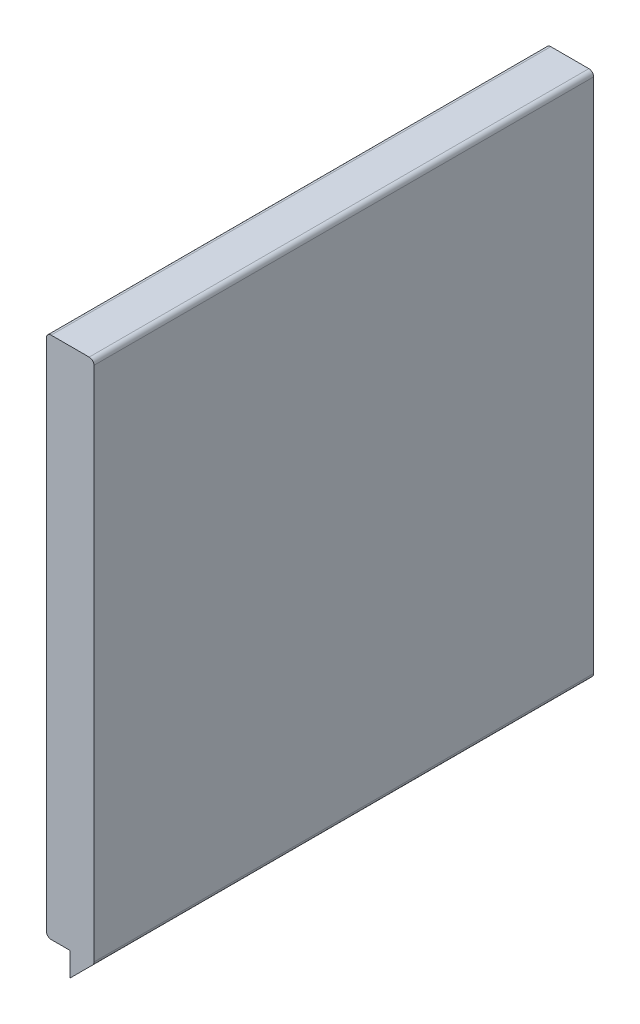
SolidWorks part; units mm, degrees
ref_plane "Front Plane" through (0, 0, 0) normal (0, 0, 1) x (1, 0, 0)
ref_plane "Top Plane" through (0, 0, 0) normal (0, 1, 0) x (1, 0, 0)
ref_plane "Right Plane" through (0, 0, 0) normal (1, 0, 0) x (0, 0, -1)
sketch "Sketch1" plane through (0, 0, 0) normal (0, 0, 1) x (1, 0, 0)
  line L1 (5, -55) -> (5, -60)
  line L2 (5, -60) -> (10, -55)
  line L3 (0, 55) -> (0, -55)
  line L4 (0, -55) -> (5, -55)
  line L5 (10, -55) -> (10, 55)
  line L6 (10, 55) -> (0, 55)
  point P6 (0, 0)
  point P7 (0, 0)
  point P9 (0, 0)
  dimension "D1" = 5
  dimension "D2" = 10
  dimension "D3" = 5
  dimension "D4" = 110
extrude "Boss-Extrude1" add sketch "Sketch1" along normal mid plane 105
fillet "Fillet1" radius 1 4 edges at (0, 55, 0) (0, -55, 0) (10, 55, 0) (10, -55, 0)
